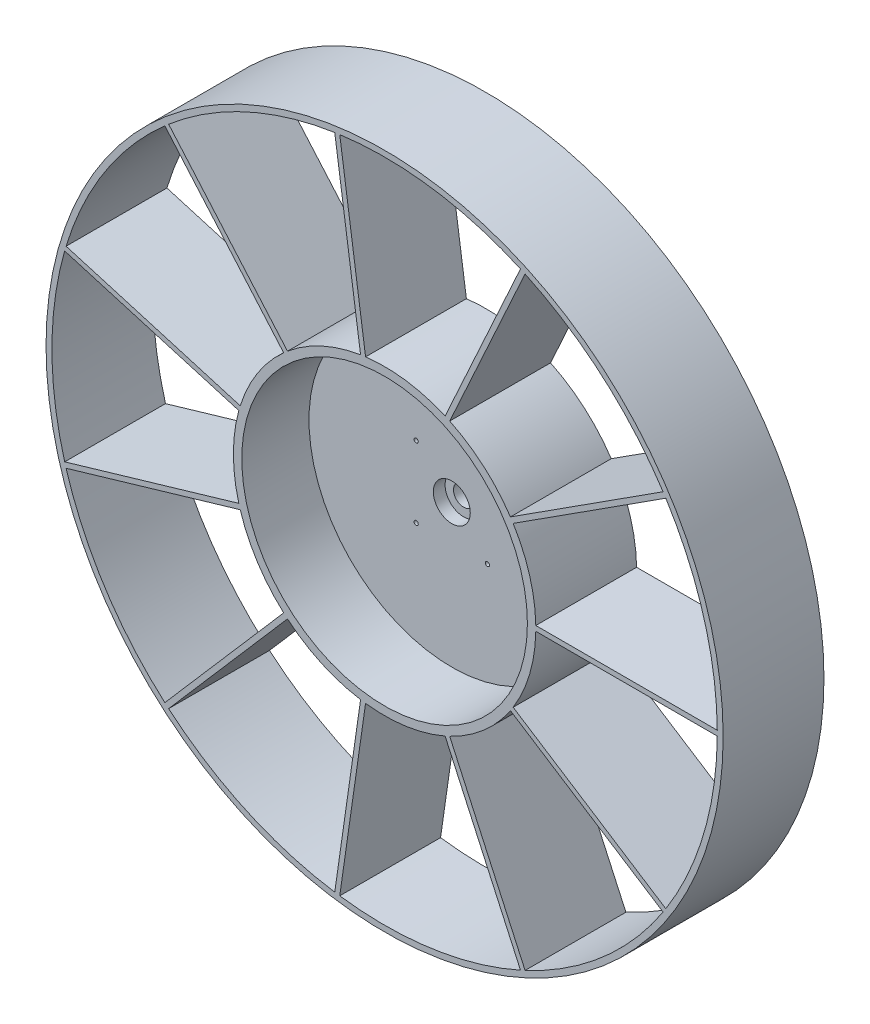
SolidWorks part; units mm, degrees
ref_plane "Front Plane" through (0, 0, 0) normal (0, 0, 1) x (1, 0, 0)
ref_plane "Top Plane" through (0, 0, 0) normal (0, 1, 0) x (1, 0, 0)
ref_plane "Right Plane" through (0, 0, 0) normal (1, 0, 0) x (0, 0, -1)
sketch "Sketch1" plane through (0, 0, 0) normal (0, 0, 1) x (1, 0, 0)
  circle A0 centre (0, 0) radius 201.5
  circle A1 centre (0, 0) radius 198
extrude "Ring" add sketch "Sketch1" along normal blind 60
sketch "Sketch2" plane through (0, 0, 0) normal (0, 0, 1) x (1, 0, 0)
  circle A0 centre (0, 0) radius 90
extrude "Floor" add sketch "Sketch2" along normal blind 20
ref_plane "Plane_z20" through (0, 0, 20) normal (0, 0, 1) x (1, 0, 0)
sketch "Sketch3" plane through (0, 0, 20) normal (0, 0, 1) x (1, 0, 0)
  circle A0 centre (0, 0) radius 90
  circle A1 centre (0, 0) radius 85
extrude "Hub_tube" add sketch "Sketch3" along normal blind 40
sketch "Sketch4" plane through (0, 0, 0) normal (0, 0, 1) x (1, 0, 0)
  line L0 (89, -1.5) -> (199, -1.5)
  line L1 (199, -1.5) -> (199, 1.5)
  line L2 (199, 1.5) -> (89, 1.5)
  line L3 (89, 1.5) -> (89, -1.5)
  line L4 (75.6825, 46.8552) -> (168.2204, 106.3256)
  line L5 (168.2204, 106.3256) -> (166.5985, 108.8494)
  line L6 (166.5985, 108.8494) -> (74.0606, 49.3789)
  line L7 (74.0606, 49.3789) -> (75.6825, 46.8552)
  line L8 (38.3364, 80.3341) -> (84.032, 180.3936)
  line L9 (84.032, 180.3936) -> (81.3031, 181.6399)
  line L10 (81.3031, 181.6399) -> (35.6075, 81.5804)
  line L11 (35.6075, 81.5804) -> (38.3364, 80.3341)
  line L12 (-11.1813, 88.3076) -> (-26.8359, 197.1879)
  line L13 (-26.8359, 197.1879) -> (-29.8054, 196.761)
  line L14 (-29.8054, 196.761) -> (-14.1508, 87.8806)
  line L15 (-14.1508, 87.8806) -> (-11.1813, 88.3076)
  line L16 (-57.149, 68.244) -> (-129.1837, 151.3765)
  line L17 (-129.1837, 151.3765) -> (-131.4509, 149.4119)
  line L18 (-131.4509, 149.4119) -> (-59.4162, 66.2794)
  line L19 (-59.4162, 66.2794) -> (-57.149, 68.244)
  line L20 (-84.9723, 26.5134) -> (-190.5165, 57.504)
  line L21 (-190.5165, 57.504) -> (-191.3617, 54.6255)
  line L22 (-191.3617, 54.6255) -> (-85.8175, 23.635)
  line L23 (-85.8175, 23.635) -> (-84.9723, 26.5134)
  line L24 (-85.8175, -23.635) -> (-191.3617, -54.6255)
  line L25 (-191.3617, -54.6255) -> (-190.5165, -57.504)
  line L26 (-190.5165, -57.504) -> (-84.9723, -26.5134)
  line L27 (-84.9723, -26.5134) -> (-85.8175, -23.635)
  line L28 (-59.4162, -66.2794) -> (-131.4509, -149.4119)
  line L29 (-131.4509, -149.4119) -> (-129.1837, -151.3765)
  line L30 (-129.1837, -151.3765) -> (-57.149, -68.244)
  line L31 (-57.149, -68.244) -> (-59.4162, -66.2794)
  line L32 (-14.1508, -87.8806) -> (-29.8054, -196.761)
  line L33 (-29.8054, -196.761) -> (-26.8359, -197.1879)
  line L34 (-26.8359, -197.1879) -> (-11.1813, -88.3076)
  line L35 (-11.1813, -88.3076) -> (-14.1508, -87.8806)
  line L36 (35.6075, -81.5804) -> (81.3031, -181.6399)
  line L37 (81.3031, -181.6399) -> (84.032, -180.3936)
  line L38 (84.032, -180.3936) -> (38.3364, -80.3341)
  line L39 (38.3364, -80.3341) -> (35.6075, -81.5804)
  line L40 (74.0606, -49.3789) -> (166.5985, -108.8494)
  line L41 (166.5985, -108.8494) -> (168.2204, -106.3256)
  line L42 (168.2204, -106.3256) -> (75.6825, -46.8552)
  line L43 (75.6825, -46.8552) -> (74.0606, -49.3789)
extrude "Vanes" add sketch "Sketch4" along normal blind 60
sketch "Sketch5" plane through (0, 0, 0) normal (0, 0, 1) x (1, 0, 0)
  circle A0 centre (0, 0) radius 6
extrude "Bore" cut sketch "Sketch5" along normal blind 20
sketch "Sketch6" plane through (0, 0, 0) normal (0, 0, 1) x (1, 0, 0)
  circle A0 centre (0, 0) radius 11
extrude "Bearing_seat_low" cut sketch "Sketch6" along normal blind 7
ref_plane "Plane_z13" through (0, 0, 13) normal (0, 0, 1) x (1, 0, 0)
sketch "Sketch7" plane through (0, 0, 13) normal (0, 0, 1) x (1, 0, 0)
  circle A0 centre (0, 0) radius 11
extrude "Bearing_seat_high" cut sketch "Sketch7" along normal blind 7
ref_plane "Plane_z12" through (0, 0, 12) normal (0, 0, 1) x (1, 0, 0)
sketch "Sketch8" plane through (0, 0, 12) normal (0, 0, 1) x (1, 0, 0)
  circle A0 centre (21.2132, 21.2132) radius 1.25
  circle A1 centre (-21.2132, 21.2132) radius 1.25
  circle A2 centre (-21.2132, -21.2132) radius 1.25
  circle A3 centre (21.2132, -21.2132) radius 1.25
extrude "Grommet_screws" cut sketch "Sketch8" along normal blind 8
